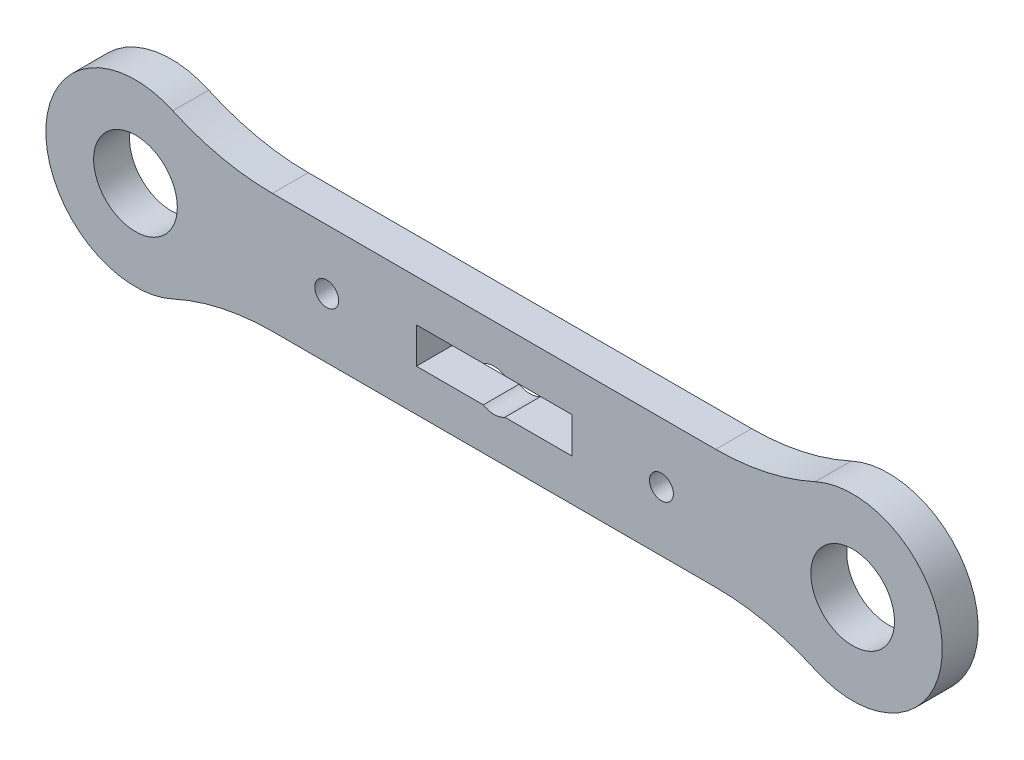
SolidWorks part; units mm, degrees
ref_plane "Plano frontal" through (0, 0, 0) normal (0, 0, 1) x (1, 0, 0)
ref_plane "Plano superior" through (0, 0, 0) normal (0, 1, 0) x (1, 0, 0)
ref_plane "Plano direito" through (0, 0, 0) normal (1, 0, 0) x (0, 0, -1)
sketch "Esboço1" plane through (0, 0, 0) normal (0, 0, 1) x (1, 0, 0)
  line L0 (5.5902, -5) -> (54.4098, -5)
  line L1 (0, 0) -> (60, 0) construction
  line L2 (5.5902, 5) -> (54.4098, 5)
  line L3 (0, 5) -> (80, 5) construction
  line L4 (0, -5) -> (80, -5) construction
  line L5 (30, 5) -> (30, -5) construction
  line L6 (30.9014, 1.5) -> (36.5, 1.5)
  line L7 (0, 0) -> (80, 0) construction
  line L8 (23.5, 1.5) -> (29.0986, 1.5)
  line L9 (23.5, 1.5) -> (23.5, -1.5)
  line L10 (23.5, -1.5) -> (29.0986, -1.5)
  line L11 (36.5, 1.5) -> (36.5, -1.5)
  line L12 (23.5, 1.5) -> (36.5, -1.5) construction
  line L13 (23.5, -1.5) -> (36.5, 1.5) construction
  line L14 (30.9014, -1.5) -> (36.5, -1.5)
  circle A0 centre (44, 0) radius 1
  circle A1 centre (16, 0) radius 1
  arc A2 (29.0986, -1.5) -> (30.9014, -1.5) centre (30, 0) ccw
  arc A3 (5.5902, 5) -> (5.5902, -5) centre (0, 0) ccw
  arc A4 (30.9014, 1.5) -> (29.0986, 1.5) centre (30, 0) ccw
  circle A13 centre (0, 0) radius 3.5
  arc A22 (54.4098, 5) -> (54.4098, -5) centre (60, 0) cw
  circle A25 centre (60, 0) radius 3.5
  point P14 (30, 0)
  point P15 (30, 0)
  point P32 (0, 0)
  dimension "D1" = 3
  dimension "D3" = 2
  dimension "D4" = 16
  dimension "D6" = 7
  dimension "D8" = 15
  dimension "D9" = 13
  dimension "D10" = 3.5
  dimension "D2" = 5
  dimension "D5" = 5
  dimension "D7" = 30
extrude "Ressalto-extrusão1" add sketch "Esboço1" along normal blind 3
fillet "Filete1" radius 20 4 edges at (5.5902, -5, 1.5) (54.4098, -5, 1.5) (54.4098, 5, 1.5) (5.5902, 5, 1.5)
